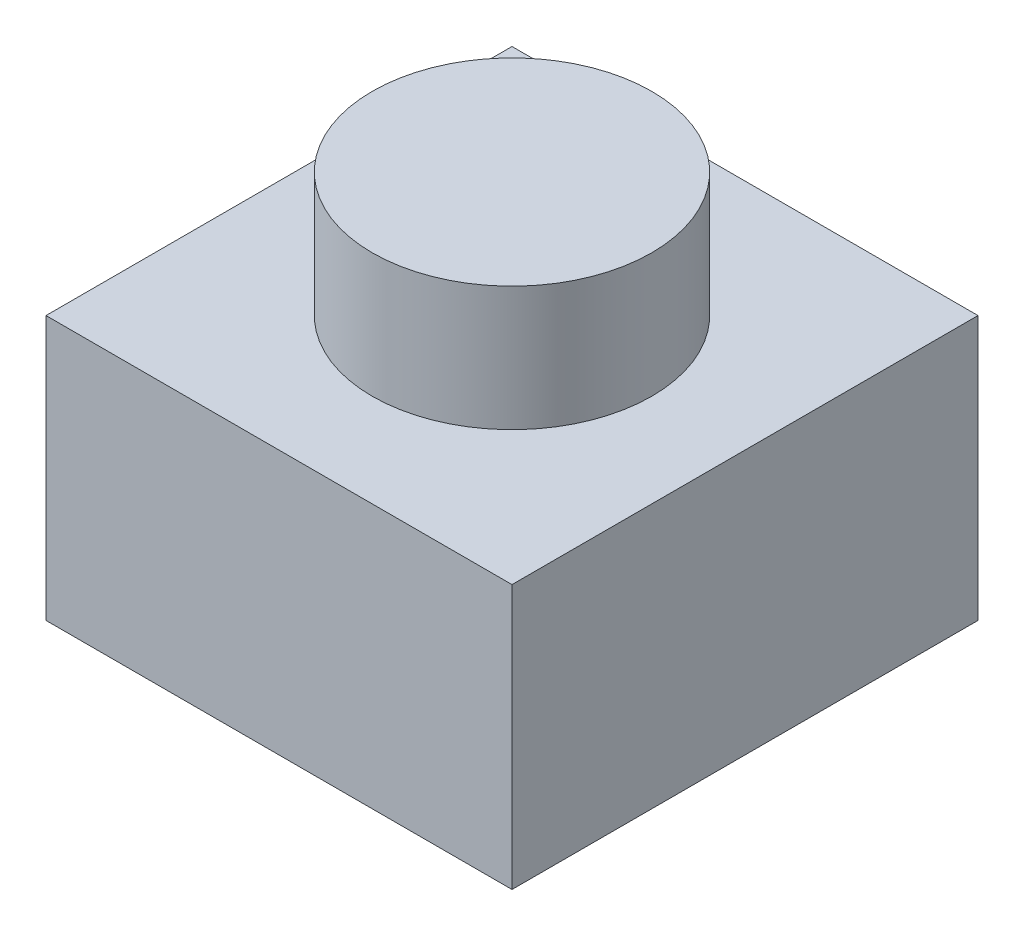
SolidWorks part; units mm, degrees
ref_plane "Front Plane" through (0, 0, 0) normal (0, 0, 1) x (1, 0, 0)
ref_plane "Top Plane" through (0, 0, 0) normal (0, 1, 0) x (1, 0, 0)
ref_plane "Right Plane" through (0, 0, 0) normal (1, 0, 0) x (0, 0, -1)
sketch "Sketch1" plane through (0, 0, 0) normal (0, 1, 0) x (1, 0, 0)
  line L1 (0, 0) -> (6, 0)
  line L2 (0, 0) -> (0, 6)
  line L3 (0, 6) -> (6, 6)
  line L4 (6, 0) -> (6, 6)
  dimension "D1" = 6
  dimension "D2" = 6
extrude "Boss-Extrude1" add sketch "Sketch1" along normal blind 3.4
sketch "Sketch2" plane through (0, 3.4, 0) normal (0, 1, 0) x (1, 0, 0)
  line L0 (0, 0) -> (6, 6) construction
  circle A0 centre (3, 3) radius 1.8
  dimension "D1" = 3.6
extrude "Boss-Extrude2" add sketch "Sketch2" along normal blind 1.6
